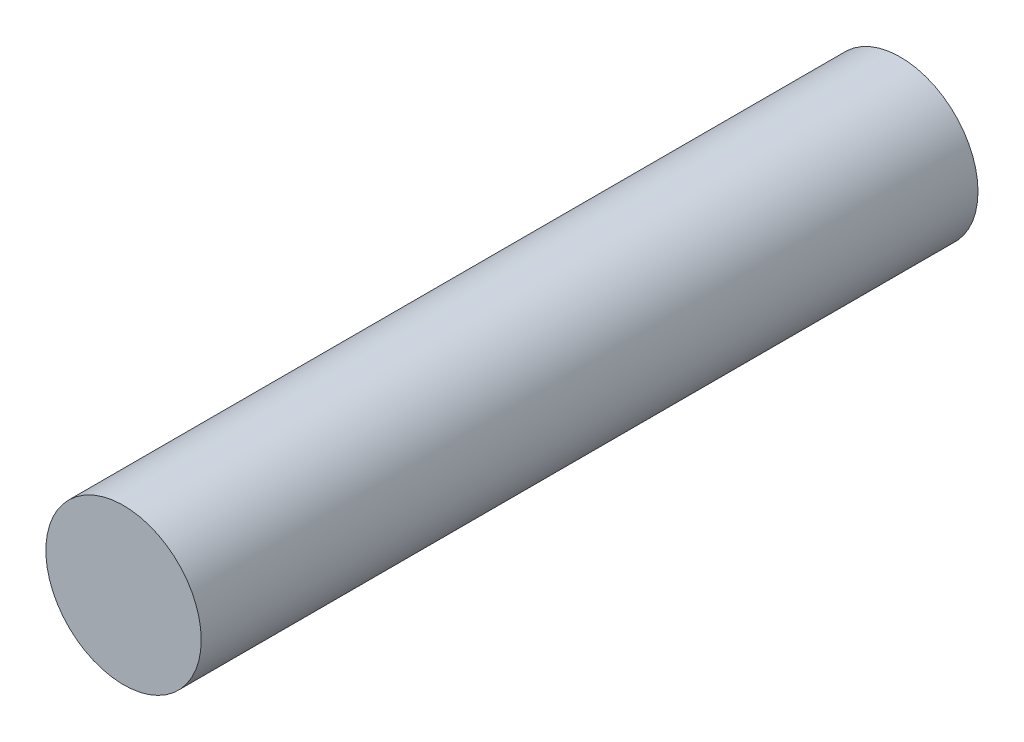
SolidWorks part; units mm, degrees
ref_plane "Front Plane" through (0, 0, 0) normal (0, 0, 1) x (1, 0, 0)
ref_plane "Top Plane" through (0, 0, 0) normal (0, 1, 0) x (1, 0, 0)
ref_plane "Right Plane" through (0, 0, 0) normal (1, 0, 0) x (0, 0, -1)
sketch "Sketch1" plane through (0, 0, 0) normal (0, 0, 1) x (1, 0, 0)
  circle A0 centre (-35.21, 21.8777) radius 0.8
  dimension "D1" = 1.6
extrude "Boss-Extrude1" add sketch "Sketch1" along normal blind 8 contours A0
ref_point "Point1"
